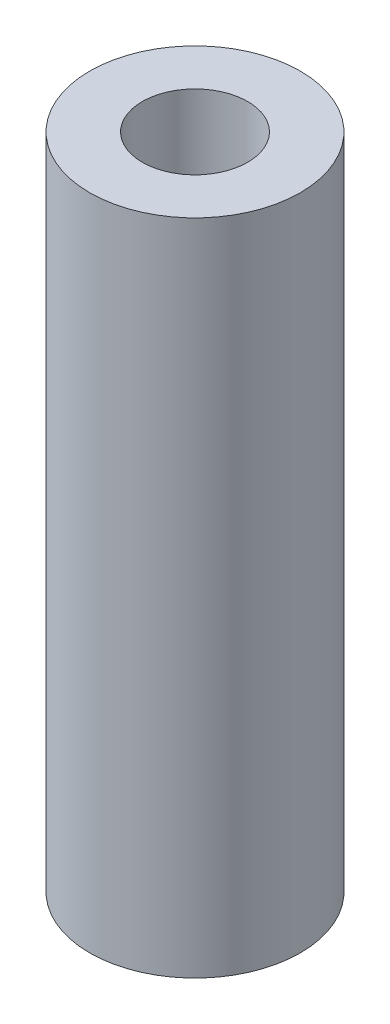
SolidWorks part; units mm, degrees
material "1060 Alloy"
ref_plane "Front Plane" through (0, 0, 0) normal (0, 0, 1) x (1, 0, 0)
ref_plane "Top Plane" through (0, 0, 0) normal (0, 1, 0) x (1, 0, 0)
ref_plane "Right Plane" through (0, 0, 0) normal (1, 0, 0) x (0, 0, -1)
sketch "Sketch1" plane through (0, 0, 0) normal (0, 1, 0) x (1, 0, 0)
  circle A0 centre (0, 0) radius 2
  circle A1 centre (0, 0) radius 4
  dimension "D1" = 4
  dimension "D2" = 8
extrude "Boss-Extrude1" add sketch "Sketch1" along normal blind 25
